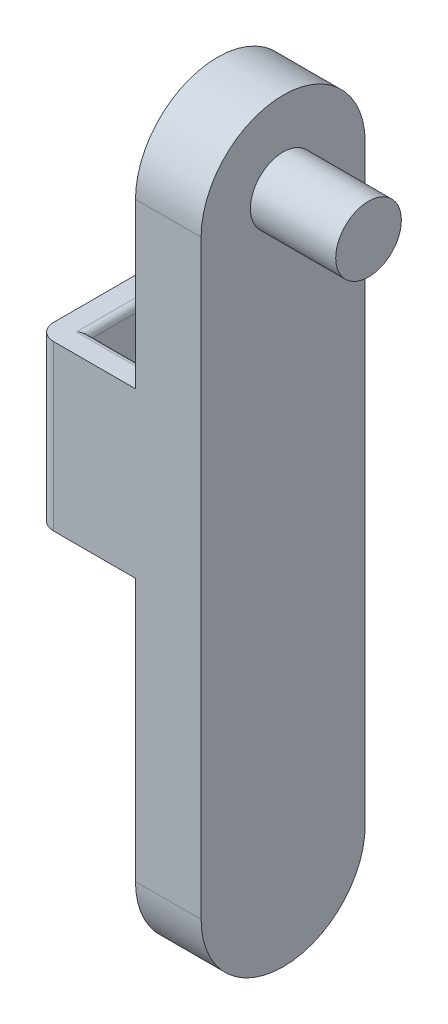
SolidWorks part; units mm, degrees
ref_plane "Front Plane" through (0, 0, 0) normal (0, 0, 1) x (1, 0, 0)
ref_plane "Top Plane" through (0, 0, 0) normal (0, 1, 0) x (1, 0, 0)
ref_plane "Right Plane" through (0, 0, 0) normal (1, 0, 0) x (0, 0, -1)
sketch "Sketch1" plane through (0, 0, 0) normal (1, 0, 0) x (0, 0, -1)
  line L0 (-17.2349, 15.5155) -> (-17.2349, -2.4845)
  line L1 (-12.2349, 15.5155) -> (-12.2349, -2.4845)
  arc A0 (-17.2349, 15.5155) -> (-12.2349, 15.5155) centre (-14.7349, 15.5155) cw
  arc A1 (-12.2349, -2.4845) -> (-17.2349, -2.4845) centre (-14.7349, -2.4845) cw
  dimension "D1" = 18
  dimension "D2" = 5
extrude "Boss-Extrude1" add sketch "Sketch1" along normal blind 2
sketch "Sketch2" plane through (2, 0, 0) normal (1, 0, 0) x (0, 0, -1)
  circle A0 centre (-14.7349, 15.5155) radius 1
  dimension "D1" = 2
extrude "Boss-Extrude2" add sketch "Sketch2" along normal blind 2.6
sketch "Sketch3" plane through (0, 0, 12.2349) normal (0, 0, -1) x (-1, 0, 0)
  line L0 (0, -2.4845) -> (0, 15.5155) construction
  line L1 (0, 10.5155) -> (3, 10.5155)
  line L2 (0, 10.5155) -> (0, 5.5155)
  line L3 (0, 5.5155) -> (3, 5.5155)
  line L4 (3, 10.5155) -> (3, 5.5155)
  line L5 (-2, 15.5155) -> (0, 15.5155) construction
  dimension "D1" = 3
  dimension "D2" = 5
  dimension "D3" = 5
extrude "Boss-Extrude3" add sketch "Sketch3" against normal up to surface (5 mm away) up to face at (1, 6.5155, 17.2349)
sketch "Sketch4" plane through (0, 10.5155, 0) normal (0, 1, 0) x (1, 0, 0)
  line L0 (0, -17.2349) -> (-3, -17.2349) construction
  line L1 (-0.8, -16.4349) -> (-2.2, -16.4349)
  line L2 (-0.8, -16.4349) -> (-0.8, -13.0349)
  line L3 (-0.8, -13.0349) -> (-2.2, -13.0349)
  line L4 (-2.2, -16.4349) -> (-2.2, -13.0349)
  line L5 (-3, -12.2349) -> (0, -12.2349) construction
  line L6 (-3, -17.2349) -> (-3, -12.2349) construction
  line L7 (0, -17.2349) -> (0, -12.2349) construction
  dimension "D1" = 0.8
  dimension "D2" = 0.8
  dimension "D3" = 0.8
  dimension "D4" = 0.8
extrude "Cut-Extrude1" cut sketch "Sketch4" against normal through all
fillet "Fillet1" radius 0.5 2 edges at (-3, 8.0155, 17.2349) (-3, 8.0155, 12.2349)
fillet "Fillet2" radius 0.2 8 edges at (-1.5, 5.5155, 13.0349) (-2.2, 5.5155, 14.7349) (-1.5, 5.5155, 16.4349) (-0.8, 5.5155, 14.7349) (-2.2, 10.5155, 14.7349) (-1.5, 10.5155, 16.4349) (-1.5, 10.5155, 13.0349) (-0.8, 10.5155, 14.7349)
